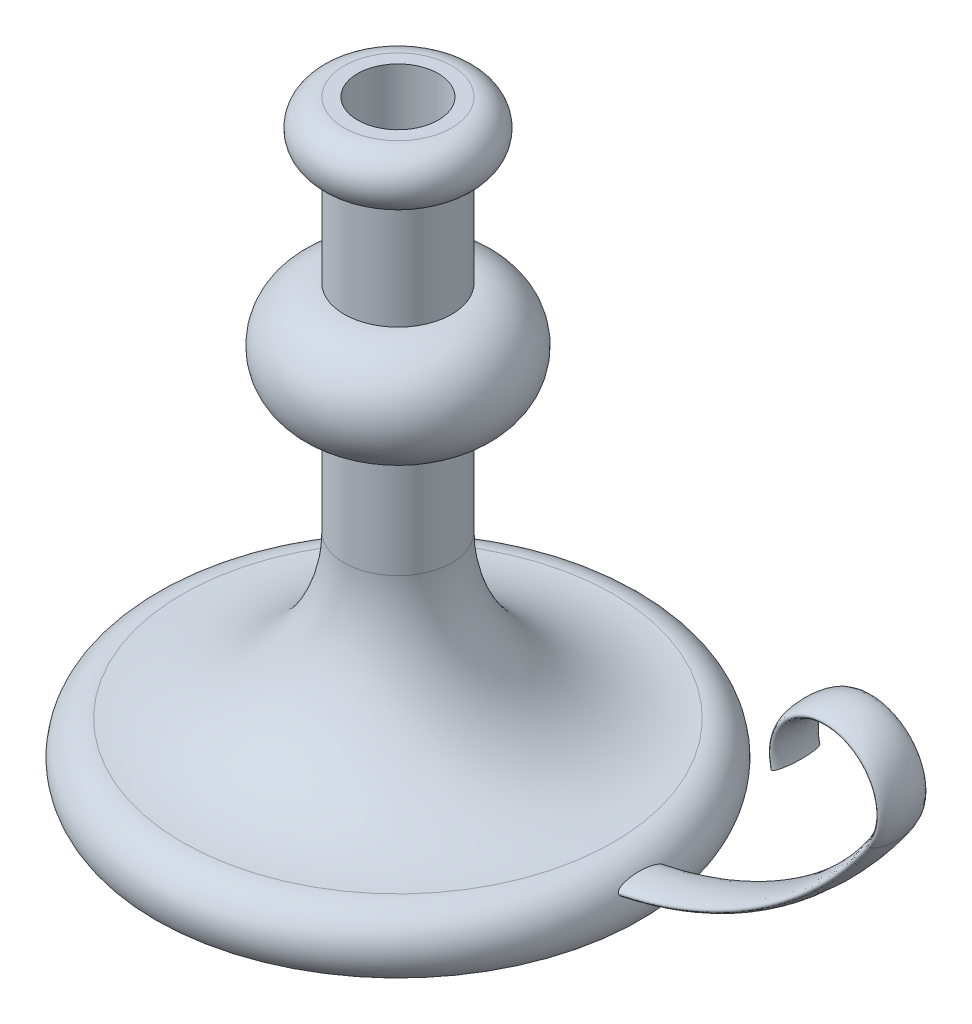
SolidWorks part; units mm, degrees
ref_plane "Alzado" through (0, 0, 0) normal (0, 0, 1) x (1, 0, 0)
ref_plane "Planta" through (0, 0, 0) normal (0, 1, 0) x (1, 0, 0)
ref_plane "Vista lateral" through (0, 0, 0) normal (1, 0, 0) x (0, 0, -1)
sketch "Croquis1" plane through (0, 0, 0) normal (0, 0, 1) x (1, 0, 0)
  line L0 (2286, 0) -> (0, 0)
  line L1 (0, 0) -> (0, 5588)
  line L2 (0, 5588) -> (508, 5588)
  line L3 (508, 5080) -> (508, 4064)
  line L4 (508, 3048) -> (508, 2032)
  arc A0 (508, 5588) -> (508, 5080) centre (508, 5334) cw
  arc A1 (508, 4064) -> (508, 3048) centre (508, 3556) cw
  arc A2 (508, 2032) -> (2032, 508) centre (2032, 2032) ccw
  arc A3 (2032, 508) -> (2286, 0) centre (2032, 190.5) cw
  dimension "D4" = 254
  dimension "D6" = 508
  dimension "D7" = 1524
  dimension "D8" = 2032
  dimension "D9" = 317.5
  dimension "D1" = 2286
  dimension "D2" = 5588
  dimension "D3" = 508
  dimension "D5" = 1016
revolve "Revolución1" add sketch "Croquis1" angle 360 about L1
sketch "Croquis2" plane through (0, 0, 0) normal (1, 0, 0) x (0, 0, -1)
  ellipse E0 centre (0, 254) end of major axis (222.25, 254) minor radius 63.5
  dimension "D1" = 444.5
  dimension "D2" = 127
  dimension "D3" = 254
sketch "Croquis3" plane through (0, 0, 0) normal (0, 0, 1) x (1, 0, 0)
  line L0 (0, 254) -> (1524, 254)
  arc A0 (1524, 254) -> (4663.2386, 1905) centre (1524, 4064) ccw
  arc A1 (4663.2386, 1905) -> (3752.1452, 2068.4483) centre (4244.6735, 2192.8667) ccw
  dimension "D2" = 3810
  dimension "D3" = 508
  dimension "D1" = 1524
  dimension "D4" = 1651
sweep "Barrer2" add profiles "Croquis2" path "Croquis3"
sketch "Croquis4" plane through (0, 5588, 0) normal (0, 1, 0) x (1, 0, 0)
  circle A0 centre (0, 0) radius 381
  dimension "D1" = 762
extrude "Cortar-Extruir1" cut sketch "Croquis4" against normal blind 581.914
